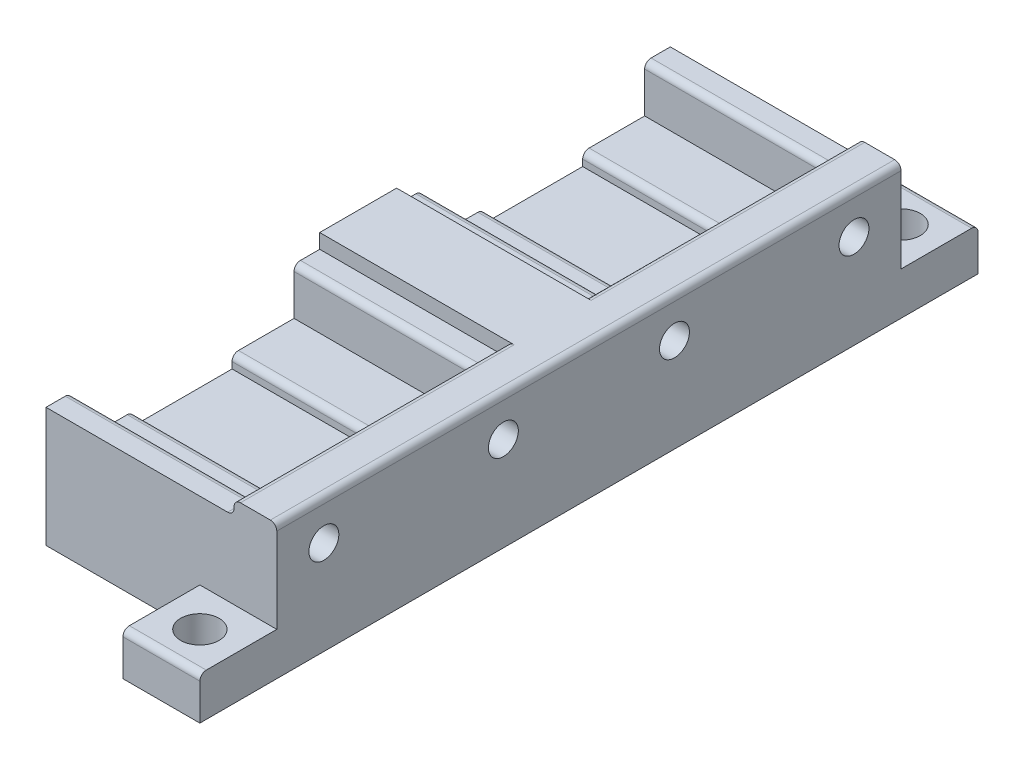
SolidWorks part; units mm, degrees
ref_plane "Front" through (0, 0, 0) normal (0, 0, 1) x (1, 0, 0)
ref_plane "Top" through (0, 0, 0) normal (0, 1, 0) x (1, 0, 0)
ref_plane "Right" through (0, 0, 0) normal (1, 0, 0) x (0, 0, -1)
sketch "Sketch1" plane through (0, 0, 0) normal (1, 0, 0) x (0, 0, -1)
  line L0 (-13.0089, 0) -> (13.0089, 0)
  line L1 (13.0089, 0) -> (13.0089, 8.5)
  line L2 (13.0089, 8.5) -> (5.7589, 8.5)
  line L3 (5.7589, 8.5) -> (5.7589, 7)
  line L4 (5.7589, 7) -> (-5.7589, 7)
  line L5 (-5.7589, 7) -> (-5.7589, 8.5)
  line L6 (-5.7589, 8.5) -> (-13.0089, 8.5)
  line L7 (-13.0089, 8.5) -> (-13.0089, 0)
  dimension "D1" = 8.5
  dimension "D2" = 7.25
  dimension "D3" = 26.0178
  dimension "D4" = 1.5
extrude "Boss-Extrude1" add sketch "Sketch1" along normal mid plane 22
sketch "Sketch3" plane through (0, 0, 0) normal (0, -1, 0) x (1, 0, 0)
  line L1 (-11, -13.0089) -> (11, -13.0089)
  line L2 (-11, -13.0089) -> (-11, -16.0089)
  line L3 (-11, -16.0089) -> (11, -16.0089)
  line L4 (11, -13.0089) -> (11, -16.0089)
  line L5 (-11, 13.0089) -> (11, 13.0089)
  line L6 (-11, 13.0089) -> (-11, 16.0089)
  line L7 (-11, 16.0089) -> (11, 16.0089)
  line L8 (11, 13.0089) -> (11, 16.0089)
  dimension "D1" = 3
  dimension "D2" = 22
  dimension "D3" = 3
  dimension "D4" = 22
extrude "Boss-Extrude2" add sketch "Sketch3" against normal blind 14
sketch "Sketch4" plane through (11, 0, 0) normal (1, 0, 0) x (0, 0, -1)
  line L0 (0, 0) -> (0, 15.7) construction
  line L1 (-16.0089, 0) -> (16.0089, 0) construction
  line L2 (-8.8, 15.7) -> (-16.0089, 15.7)
  line L3 (-16.0089, 14) -> (-16.0089, 0) construction
  line L4 (-16.0089, 15.7) -> (-16.0089, 0)
  line L5 (-16.0089, 0) -> (16.0089, 0)
  line L6 (16.0089, 0) -> (16.0089, 15.7)
  line L7 (16.0089, 14) -> (16.0089, 0) construction
  line L8 (16.0089, 15.7) -> (-8.8, 15.7)
  dimension "D2" = 15.7
extrude "Boss-Extrude3" add sketch "Sketch4" along normal blind 5
sketch "Sketch5" plane through (16, 0, 0) normal (1, 0, 0) x (0, 0, -1)
  line L0 (-16.0089, 11) -> (-10.5, 11) construction
  line L1 (-16.0089, 15.7) -> (-16.0089, 0) construction
  line L2 (-10.5, 11) -> (-10.5, 0) construction
  line L3 (-16.0089, 0) -> (16.0089, 0) construction
  line L4 (0, 0) -> (0, 15.7) construction
  line L5 (16.0089, 15.7) -> (-16.0089, 15.7) construction
  circle A0 centre (-10.5, 11) radius 1.75
  circle A1 centre (10.5, 11) radius 1.75
  dimension "D3" = 3.5
  dimension "D1" = 5.5089
  dimension "D2" = 11
extrude "Cut-Extrude1" cut sketch "Sketch5" against normal through all
sketch "Sketch6" plane through (0, 0, 0) normal (0, -1, 0) x (1, 0, 0)
  line L15 (16, 16.0089) -> (7, 16.0089)
  line L20 (16, 16.0089) -> (16, 25.0089)
  line L21 (16, 25.0089) -> (7, 25.0089)
  line L22 (7, 16.0089) -> (7, 25.0089)
  dimension "D3" = 9
  dimension "D4" = 9
extrude "Boss-Extrude4" add sketch "Sketch6" against normal blind 5
sketch "Sketch10" plane through (0, 0, 0) normal (0, -1, 0) x (1, 0, 0)
  line L0 (7, 20.5089) -> (16, 20.5089) construction
  line L1 (7, 25.0089) -> (7, 16.0089) construction
  line L2 (16, 25.0089) -> (16, -16.0089) construction
  line L3 (11.5, 25.0089) -> (11.5, 20.5089) construction
  line L4 (16, 25.0089) -> (7, 25.0089) construction
  circle A0 centre (11.5, 20.5089) radius 2.25
  dimension "D1" = 4.5
extrude "Cut-Extrude2" cut sketch "Sketch10" against normal through all
sketch "Sketch8" plane through (0, 0, -16.0089) normal (0, 0, -1) x (-1, 0, 0)
  line L1 (11, 0) -> (-16, 0)
  line L2 (11, 0) -> (11, 15.7)
  line L3 (11, 15.7) -> (-16, 15.7)
  line L4 (-16, 0) -> (-16, 15.7)
extrude "Boss-Extrude5" add sketch "Sketch8" along normal blind 4.5
fillet "Fillet1" radius 0.75 11 edges at (11.5, 5, 25.0089) (0, 8.5, 5.7589) (0, 8.5, -5.7589) (11, 11.25, 13.0089) (11, 11.25, -13.0089) (0, 14, 13.0089) (0, 14, -13.0089) (11, 15.7, 0) (11, 14, 14.5089) (11, 14, -14.5089) (16, 15.7, -2.25)
mirror "Mirror6" about plane through (0, 0, -20.5089) normal (0, 0, -1) of bodies 133
